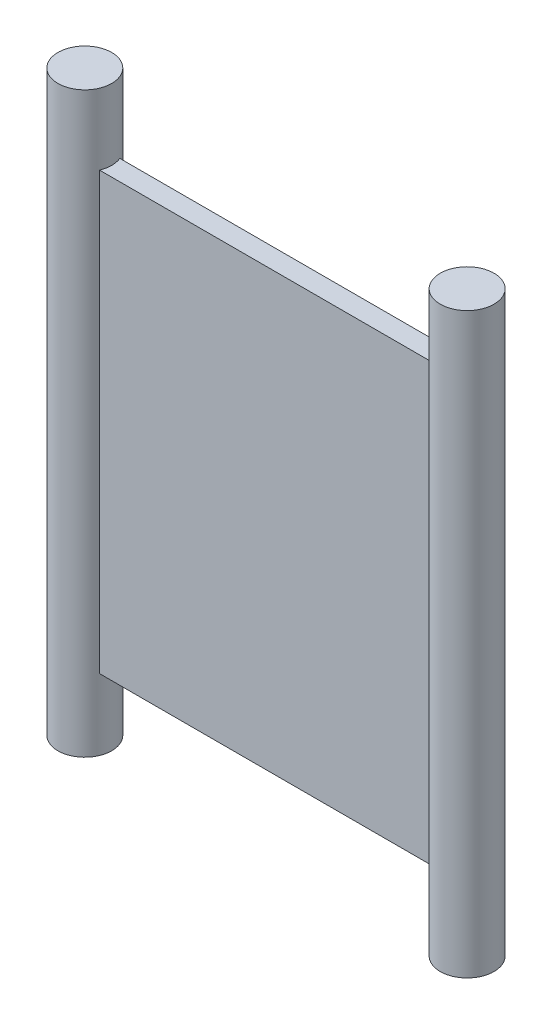
SolidWorks part; units mm, degrees
ref_plane "Front Plane" through (0, 0, 0) normal (0, 0, 1) x (1, 0, 0)
ref_plane "Top Plane" through (0, 0, 0) normal (0, 1, 0) x (1, 0, 0)
ref_plane "Right Plane" through (0, 0, 0) normal (1, 0, 0) x (0, 0, -1)
sketch "Sketch1" plane through (0, 0, 0) normal (0, 1, 0) x (1, 0, 0)
  line L1 (9.426, 0.5) -> (-9.426, 0.5)
  line L2 (9.426, 0.5) -> (9.426, -0.5)
  line L3 (9.426, -0.5) -> (-9.426, -0.5)
  line L4 (-9.426, 0.5) -> (-9.426, -0.5)
  line L5 (9.426, 0.5) -> (-9.426, -0.5) construction
  line L6 (9.426, -0.5) -> (-9.426, 0.5) construction
  point P0 (0, 0)
  dimension "D1" = 18.852
  dimension "D3" = 1
extrude "Boss-Extrude1" add sketch "Sketch1" along normal blind 21.5
ref_plane "Plane1" through (0, 10.75, 0) normal (0, 1, 0) x (1, 0, 0)
sketch "Sketch2" plane through (0, 10.75, 0) normal (0, 1, 0) x (1, 0, 0)
  line L0 (9.426, -0.5) -> (9.426, 0.5) construction
  line L1 (-9.426, 0.5) -> (-9.426, -0.5) construction
  line L2 (9.426, -0.5) -> (9.426, 0.5) construction
  line L3 (-9.426, 0.5) -> (-9.426, -0.5) construction
  circle A0 centre (-9.426, 0) radius 1.325
  circle A1 centre (9.426, 0) radius 1.325
  dimension "D1" = 2.65
extrude "Boss-Extrude2" add sketch "Sketch2" along normal mid plane 28.5
